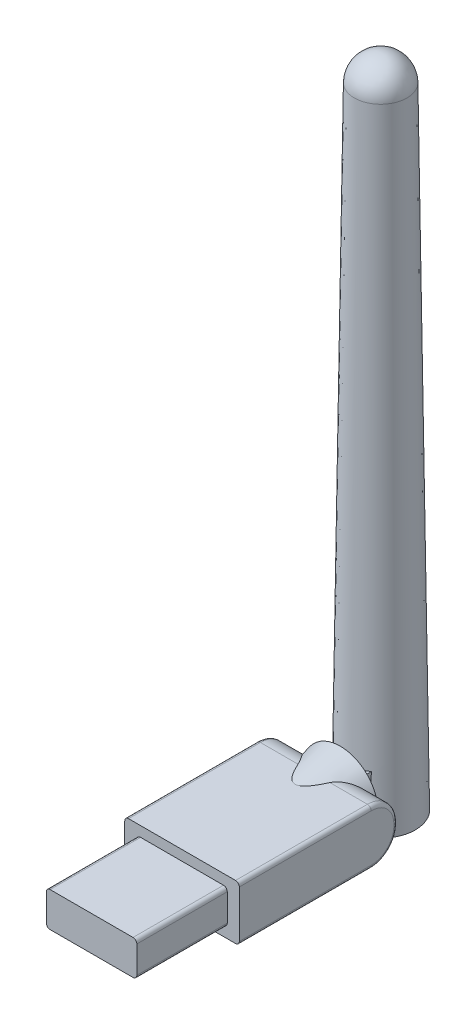
SolidWorks part; units mm, degrees
ref_plane "Front Plane" through (0, 0, 0) normal (0, 0, 1) x (1, 0, 0)
ref_plane "Top Plane" through (0, 0, 0) normal (0, 1, 0) x (1, 0, 0)
ref_plane "Right Plane" through (0, 0, 0) normal (1, 0, 0) x (0, 0, -1)
sketch "Sketch1" plane through (0, 0, 0) normal (0, 0, 1) x (1, 0, 0)
  line L1 (0, 0) -> (12, 0)
  line L2 (0, 0) -> (0, 4.6)
  line L3 (0, 4.6) -> (12, 4.6)
  line L4 (12, 0) -> (12, 4.6)
  dimension "D1" = 12
  dimension "D2" = 4.6
extrude "Boss-Extrude1" add sketch "Sketch1" along normal blind 12
sketch "Sketch2" plane through (0, 0, 0) normal (0, 0, -1) x (-1, 0, 0)
  line L0 (-12, 4.6) -> (0, 4.6) construction
  line L1 (-13.6, 5.95) -> (1.6, 5.95)
  line L2 (-13.6, 5.95) -> (-13.6, -1.3)
  line L3 (-13.6, -1.3) -> (1.6, -1.3)
  line L4 (1.6, 5.95) -> (1.6, -1.3)
  line L7 (-12, 0) -> (-12, 4.6) construction
  dimension "D1" = 7.25
  dimension "D2" = 15.2
  dimension "D3" = 1.35
  dimension "D4" = 1.6
extrude "Boss-Extrude2" add sketch "Sketch2" along normal blind 21
fillet "Fillet1" radius 3.5 2 edges at (6, -1.3, -21) (6, 5.95, -21)
sketch "Sketch4" plane through (0, 0, -21) normal (0, 0, -1) x (-1, 0, 0)
  line L0 (-13.6, -1.3) -> (1.6, -1.3) construction
  line L1 (-8.5, 4.85) -> (-3.5, 4.85)
  line L2 (-8.5, 4.85) -> (-8.5, -0.15)
  line L3 (-8.5, -0.15) -> (-3.5, -0.15)
  line L4 (-3.5, 4.85) -> (-3.5, -0.15)
  line L7 (1.6, 2.2) -> (1.6, 2.45) construction
  dimension "D1" = 5
  dimension "D2" = 5
  dimension "D3" = 1.15
  dimension "D4" = 5.1
extrude "Boss-Extrude3" add sketch "Sketch4" along normal blind 6.5 and the other way up to next
ref_plane "Plane1" through (0, 2.325, 0) normal (0, 1, 0) x (1, 0, 0)
ref_plane "Plane2" through (6, 0, 0) normal (1, 0, 0) x (0, 0, -1)
sketch "Sketch5" plane through (6, 0, 0) normal (1, 0, 0) x (0, 0, -1)
  line L0 (26.35, -2.675) -> (26.35, 84.325)
  line L1 (26.35, 84.325) -> (-8.2008, 84.325) construction
  line L2 (22.85, 80.8708) -> (21.75, -2.675)
  line L3 (21.75, -2.675) -> (26.35, -2.675)
  line L6 (21, 2.45) -> (21, 2.2) construction
  line L7 (8.36, 2.325) -> (-8.36, 2.325) construction
  arc A0 (26.35, 84.325) -> (22.85, 80.8708) centre (26.35, 80.8247) ccw
  dimension "D1" = 5.35
  dimension "D2" = 4.6
  dimension "D3" = 5
  dimension "D4" = 3.5
  dimension "D5" = 82
revolve "Revolve1" add sketch "Sketch5" angle 360 about L0
sketch "Sketch6" plane through (6, 0, 0) normal (1, 0, 0) x (0, 0, -1)
  line L0 (21, 2.325) -> (21, 7.325)
  line L1 (21, 2.45) -> (21, 2.2) construction
  line L2 (21, 7.325) -> (15, 5.95)
  line L3 (17.5, 5.95) -> (0, 5.95) construction
  line L4 (15, 5.95) -> (15, 2.325)
  line L5 (8.36, 2.325) -> (-8.36, 2.325) construction
  line L6 (15, 2.325) -> (21, 2.325)
  dimension "D1" = 5
  dimension "D2" = 6
revolve "Revolve2" add sketch "Sketch6" angle 360 about L6
fillet "Fillet2" radius 0.5 10 edges at (13.6, -1.3, -8.75) (13.6, -0.2749, -19.9749) (13.6, 2.325, -21) (13.6, 4.9249, -19.9749) (-1.6, -1.3, -8.75) (-1.6, -0.2749, -19.9749) (-1.6, 2.325, -21) (-1.6, 4.9249, -19.9749) (13.6, 5.95, -8.75) (-1.6, 5.95, -8.75)
fillet "Fillet3" radius 0.5 4 edges at (0, 0, 6) (0, 4.6, 6) (12, 0, 6) (12, 4.6, 6)
